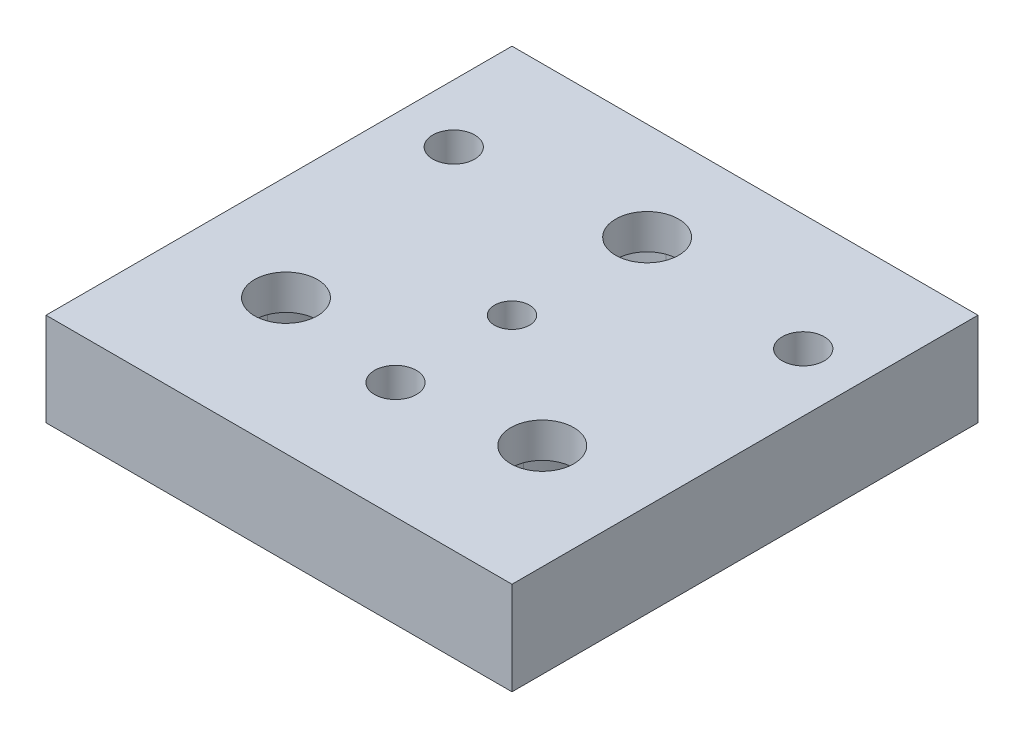
SolidWorks part; units mm, degrees
material "AISI 304"
ref_plane "Front Plane" through (0, 0, 0) normal (0, 0, 1) x (1, 0, 0)
ref_plane "Top Plane" through (0, 0, 0) normal (0, 1, 0) x (1, 0, 0)
ref_plane "Right Plane" through (0, 0, 0) normal (1, 0, 0) x (0, 0, -1)
sketch "Sketch1" plane through (0, 0, 0) normal (0, 1, 0) x (1, 0, 0)
  line L1 (-25.4, 25.4) -> (25.4, 25.4)
  line L2 (-25.4, 25.4) -> (-25.4, -25.4)
  line L3 (-25.4, -25.4) -> (25.4, -25.4)
  line L4 (25.4, 25.4) -> (25.4, -25.4)
  line L5 (-25.4, 25.4) -> (25.4, -25.4) construction
  line L6 (-25.4, -25.4) -> (25.4, 25.4) construction
  point P0 (0, 0)
  dimension "D1" = 50.8
  dimension "D2" = 50.8
extrude "Boss-Extrude1" add sketch "Sketch1" along normal blind 10.16
sketch "Sketch2" plane through (0, 10.16, 0) normal (0, 1, 0) x (1, 0, 0)
  line L0 (25.4, -25.4) -> (25.4, 25.4) construction
  line L1 (-25.4, -25.4) -> (25.4, -25.4) construction
  line L2 (25.4, 25.4) -> (-25.4, 25.4) construction
  line L4 (-25.4, 25.4) -> (-25.4, -25.4) construction
  circle A0 centre (-19.05, 12.7) radius 2.286
  circle A1 centre (19.05, 12.7) radius 2.286
  circle A2 centre (0, -12.7) radius 2.286
  dimension "D1" = 4.572
  dimension "D2" = 4.572
  dimension "D3" = 4.572
  dimension "D9" = 6.35
  dimension "D4" = 25.4
  dimension "D5" = 12.7
  dimension "D6" = 12.7
  dimension "D7" = 12.7
  dimension "D8" = 38.1
extrude "Cut-Extrude1" cut sketch "Sketch2" against normal through all
sketch "Sketch3" plane through (0, 0, 0) normal (0, -1, 0) x (1, 0, 0)
  line L0 (-13.97, 16.256) -> (-13.97, 5.08) construction
  line L1 (-6.35, 16.256) -> (-6.35, 5.08)
  line L2 (-21.59, 16.256) -> (-21.59, 5.08)
  line L3 (13.97, 16.256) -> (13.97, 5.08) construction
  line L4 (21.59, 16.256) -> (21.59, 5.08)
  line L5 (6.35, 16.256) -> (6.35, 5.08)
  line L6 (-5.588, -14.732) -> (5.588, -14.732) construction
  line L7 (-5.588, -7.112) -> (5.588, -7.112)
  line L8 (-5.588, -22.352) -> (5.588, -22.352)
  line L9 (25.4, 25.4) -> (25.4, -25.4) construction
  line L10 (-25.4, 25.4) -> (25.4, 25.4) construction
  line L11 (-25.4, -25.4) -> (-25.4, 25.4) construction
  line L12 (25.4, -25.4) -> (-25.4, -25.4) construction
  arc A0 (-6.35, 16.256) -> (-21.59, 16.256) centre (-13.97, 16.256) ccw
  arc A1 (-21.59, 5.08) -> (-6.35, 5.08) centre (-13.97, 5.08) ccw
  arc A2 (21.59, 16.256) -> (6.35, 16.256) centre (13.97, 16.256) ccw
  arc A3 (6.35, 5.08) -> (21.59, 5.08) centre (13.97, 5.08) ccw
  arc A4 (-5.588, -7.112) -> (-5.588, -22.352) centre (-5.588, -14.732) ccw
  arc A5 (5.588, -22.352) -> (5.588, -7.112) centre (5.588, -14.732) ccw
  circle A6 centre (-13.97, 10.668) radius 3.429
  circle A7 centre (13.97, 10.668) radius 3.429
  circle A8 centre (0, -14.732) radius 3.429
  point P2 (-13.97, 10.668)
  point P7 (13.97, 10.668)
  point P14 (0, -14.732)
  dimension "D5" = 10.668
  dimension "D7" = 7.62
  dimension "D8" = 7.62
  dimension "D9" = 7.62
  dimension "D10" = 6.858
  dimension "D11" = 6.858
  dimension "D12" = 6.858
  dimension "D1" = 11.43
  dimension "D2" = 14.732
  dimension "D3" = 14.732
  dimension "D4" = 11.43
  dimension "D6" = 25.4
  dimension "D13" = 11.176
  dimension "D14" = 11.176
  dimension "D15" = 11.176
extrude "Cut-Extrude2" cut sketch "Sketch3" against normal blind 6.35
sketch "Sketch4" plane through (0, 0, 0) normal (0, -1, 0) x (-1, 0, 0)
  circle A0 centre (13.97, -10.668) radius 3.429
  circle A1 centre (-13.97, -10.668) radius 3.429
  circle A2 centre (0, 14.732) radius 3.429
extrude "Cut-Extrude3" cut sketch "Sketch4" against normal through all
sketch "Sketch5" plane through (0, 10.16, 0) normal (0, 1, 0) x (1, 0, 0)
  circle A0 centre (0, 0) radius 1.905
  dimension "D1" = 3.81
extrude "Cut-Extrude5" cut sketch "Sketch5" against normal through all
